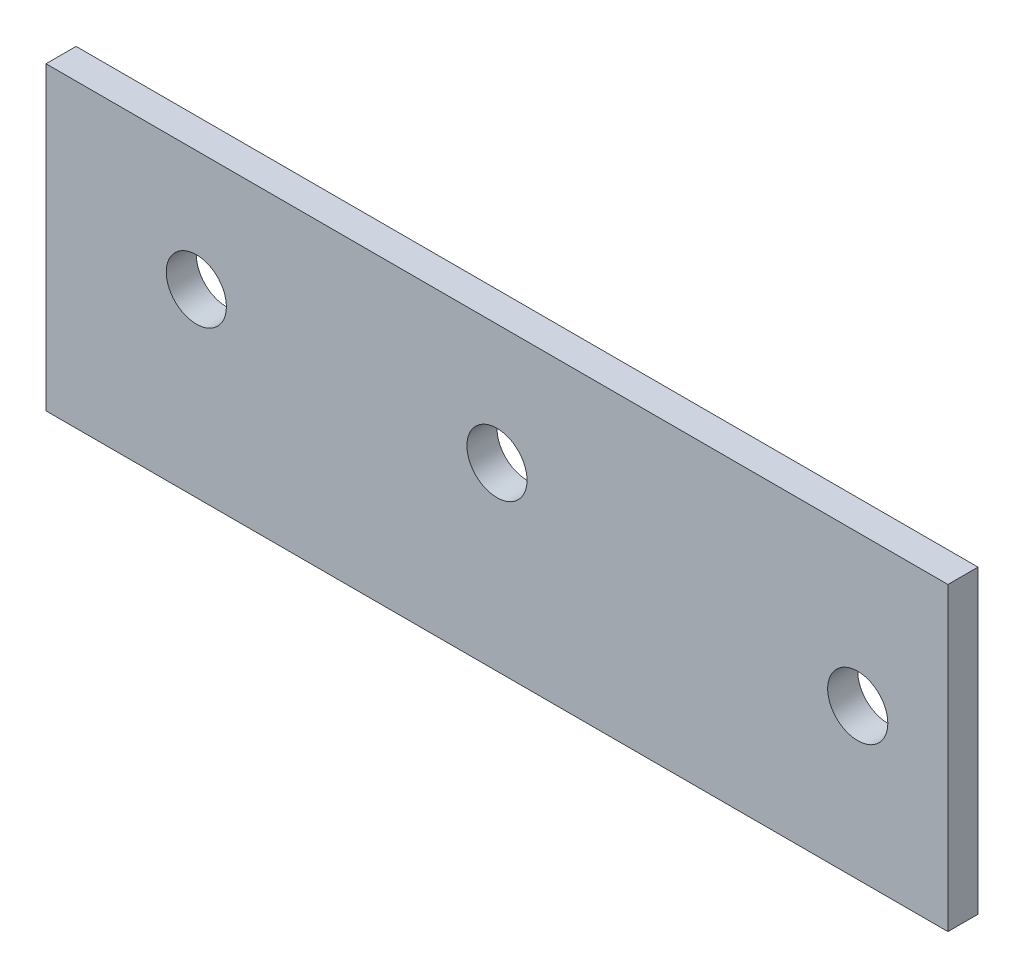
SolidWorks part; units mm, degrees
ref_plane "Plan de face" through (0, 0, 0) normal (0, 0, 1) x (1, 0, 0)
ref_plane "Plan de dessus" through (0, 0, 0) normal (0, 1, 0) x (1, 0, 0)
ref_plane "Plan de droite" through (0, 0, 0) normal (1, 0, 0) x (0, 0, -1)
sketch "Esquisse1" plane through (0, 0, 0) normal (0, 0, 1) x (1, 0, 0)
  line L1 (543.5913, 1888.0895) -> (498.5913, 1888.0895)
  line L2 (543.5913, 1888.0895) -> (543.5913, 1873.0895)
  line L3 (543.5913, 1873.0895) -> (498.5913, 1873.0895)
  line L4 (498.5913, 1888.0895) -> (498.5913, 1873.0895)
  circle A0 centre (506.0913, 1882.0895) radius 1.5
  circle A1 centre (521.0913, 1882.0895) radius 1.5
  circle A2 centre (539.0913, 1880.5895) radius 1.5
  dimension "D3" = 9
  dimension "D6" = 7.5
  dimension "D7" = 9
  dimension "D1" = 15
  dimension "D2" = 22.5
  dimension "D4" = 7.5
  dimension "D5" = 4.5
  dimension "D8" = 15
extrude "Extrusion1" add sketch "Esquisse1" along normal blind 1.5
